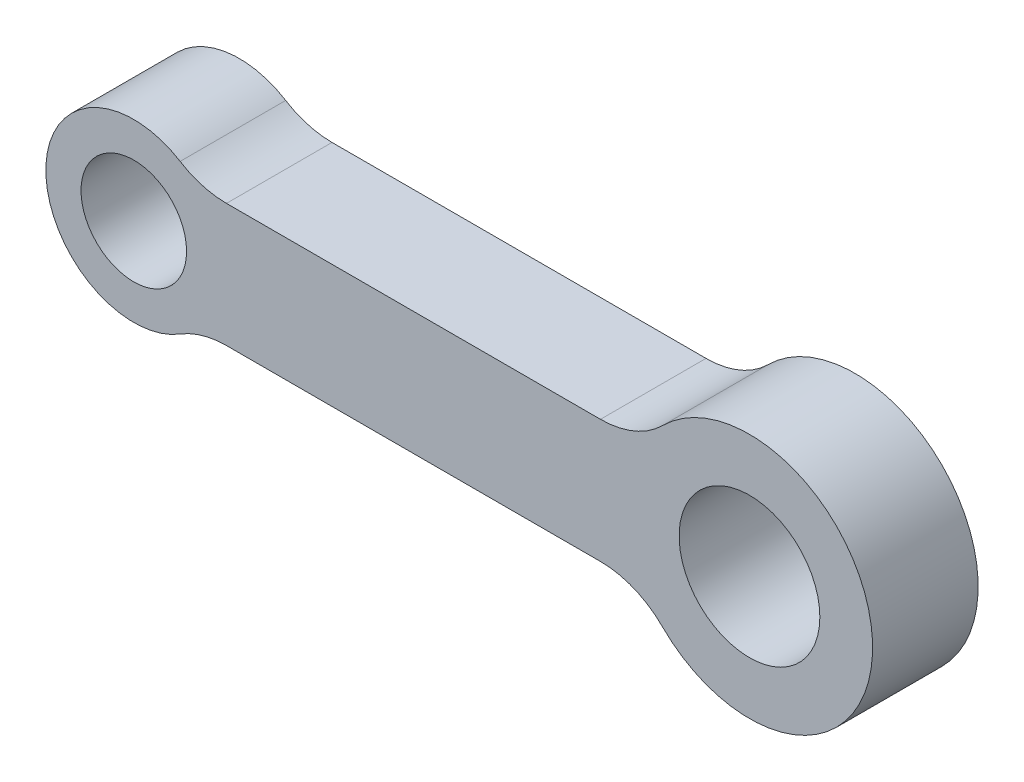
SolidWorks part; units mm, degrees
ref_plane "Front Plane" through (0, 0, 0) normal (0, 0, 1) x (1, 0, 0)
ref_plane "Top Plane" through (0, 0, 0) normal (0, 1, 0) x (1, 0, 0)
ref_plane "Right Plane" through (0, 0, 0) normal (1, 0, 0) x (0, 0, -1)
sketch "Sketch3" plane through (0, 0, 0) normal (0, 0, 1) x (1, 0, 0)
  line L1 (-17.5, 3.5) -> (17.5, 3.5)
  line L2 (-17.5, 3.5) -> (-17.5, -3.5)
  line L3 (-17.5, -3.5) -> (17.5, -3.5)
  line L4 (17.5, 3.5) -> (17.5, -3.5)
  line L5 (-17.5, 3.5) -> (17.5, -3.5) construction
  line L6 (-17.5, -3.5) -> (17.5, 3.5) construction
  circle A0 centre (-17.5, 0) radius 3
  circle A1 centre (-17.5, 0) radius 5
  circle A2 centre (17.5, 0) radius 4
  circle A3 centre (17.5, 0) radius 7
  point P0 (0, 0)
  dimension "D2" = 8
  dimension "D3" = 14
  dimension "D4" = 10
  dimension "D5" = 6
  dimension "D1" = 35
  dimension "D6" = 7
extrude "Boss-Extrude1" add sketch "Sketch3" along normal mid plane 6 contours A3 L1 A1 L3 | L1 A1 L3 L2 A0 | L3 A3 L1 A2 | L1 A3 L3 A2 | L3 A1 L1 L2 A0
fillet "Fillet1" radius 5 4 edges at (11.4378, 3.5, 0) (-13.9293, 3.5, 0) (11.4378, -3.5, 0) (-13.9293, -3.5, 0)
